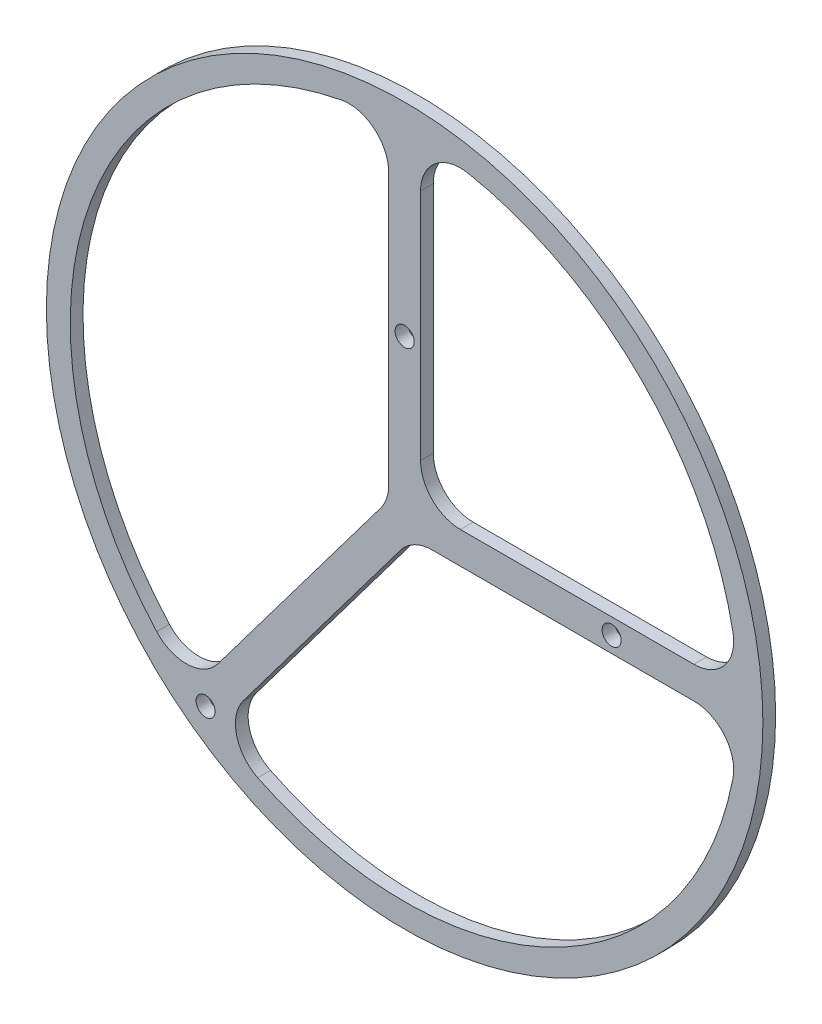
SolidWorks part; units mm, degrees
ref_plane "Front Plane" through (0, 0, 0) normal (1, 0, 0) x (0, 1, 0)
ref_plane "Top Plane" through (0, 0, 0) normal (0, 0, 1) x (0, 1, 0)
ref_plane "Right Plane" through (0, 0, 0) normal (0, 1, 0) x (-1, 0, 0)
sketch "Sketch5" plane through (0, 0, 0) normal (0, 0, 1) x (0, 1, 0)
  circle A0 centre (0, 0) radius 45
  dimension "D1" = 90
extrude "Boss-Extrude2" add sketch "Sketch5" along normal blind 1.6
sketch "Sketch2" plane through (0, 0, 0) normal (0, 0, 1) x (0, 1, 0)
  line L0 (19.5, 0) -> (0, 0) construction
  line L1 (0, 0) -> (0, -26) construction
  circle A0 centre (0, 0) radius 45
  point P0 (-42, -26)
  point P1 (0, -26)
  point P2 (19.5, 0)
  point P3 (-33.2215, 25)
  dimension "D6" = 90
  dimension "D1" = 42
  dimension "D2" = 61.5
  dimension "D3" = 26
  dimension "D4" = 51
  dimension "D5" = 51.75
hole_wizard "M2 Clearance Hole2" positions "Sketch2" profile "Sketch7" hole size "M2" standard "ANSI Metric"
sketch "Sketch7" plane through (-25, -33.2215, 0) normal (1, 0, 0) x (0, 1, 0)
  line L0 (0, 0) -> (0, 2.321)
  line L1 (0, 2.321) -> (1.2, 1.6)
  line L2 (1.2, 1.6) -> (1.2, 0)
  line L5 (1.2, 0) -> (0, 0)
  line L10 (0, 2.321) -> (-1.2, 1.6) construction
  line L11 (0, -6.35) -> (0, 107.95) construction
  dimension "Hole Dia." = 2.4
  dimension "Hole Depth" = 1.6
  dimension "Drill Angle" = 118
sketch "Sketch8" plane through (0, 0, 1.6) normal (0, 0, 1) x (1, 0, 0)
  line L0 (-25, -33.2215) -> (0, 0) construction
  line L1 (0, 0) -> (26, 0) construction
  line L2 (0, 0) -> (0, 19.5) construction
  line L3 (-25, -33.2215) -> (-25.2542, -33.5593) construction
  line L4 (26, 0) -> (42, 0) construction
  line L5 (0, 19.5) -> (0, 42) construction
  line L6 (-26.5981, -32.0189) -> (-26.8236, -32.3186)
  line L7 (-26.5981, -32.0189) -> (-2, 0.6685)
  line L8 (2, 2) -> (26, 2)
  line L9 (26, 2) -> (41.9524, 2)
  line L10 (-2, 0.6685) -> (-2, 19.5)
  line L11 (-2, 19.5) -> (-2, 41.9524)
  line L12 (-23.4019, -34.4241) -> (-23.6275, -34.7238)
  line L13 (-23.4019, -34.4241) -> (0.998, -2)
  line L14 (0.998, -2) -> (26, -2)
  line L15 (26, -2) -> (41.9524, -2)
  line L16 (2, 2) -> (2, 19.5)
  line L17 (2, 19.5) -> (2, 41.9524)
  line L19 (-26.5981, -32.0189) -> (-1.5981, 1.2026) construction
  line L20 (-2, 0) -> (-2, 19.5) construction
  line L21 (-23.4019, -34.4241) -> (1.5981, -1.2026) construction
  line L22 (0, -2) -> (26, -2) construction
  line L23 (2, 0) -> (2, 19.5) construction
  line L24 (0, 2) -> (26, 2) construction
  line L25 (-23.4019, -34.4241) -> (-23.6561, -34.7619) construction
  line L26 (-26.5981, -32.0189) -> (-26.8523, -32.3567) construction
  line L27 (26, -2) -> (42, -2) construction
  line L28 (26, 2) -> (42, 2) construction
  line L29 (-2, 19.5) -> (-2, 42) construction
  line L30 (2, 19.5) -> (2, 42) construction
  circle A2 centre (0, 0) radius 42
  circle A3 centre (0, 0) radius 42
  circle A14 centre (-25, -33.2215) radius 1.2 construction
  circle A17 centre (26, 0) radius 1.2 construction
  circle A19 centre (0, 19.5) radius 1.2 construction
  circle A20 centre (-25, -33.2215) radius 1.2
  circle A22 centre (26, 0) radius 1.2
  circle A23 centre (0, 19.5) radius 1.2
  dimension "D1" = 3
  dimension "D5" = 2
  dimension "D6" = 2
extrude "Cut-Extrude1" cut sketch "Sketch8" against normal through all contours L12 A3 L15 L14 L13 | L11 A3 L6 L7 L10 | L9 A3 L17 L16 L8
fillet "Fillet1" radius 5 9 edges at (-23.6275, -34.7238, 0.8) (-26.8236, -32.3186, 0.8) (-2, 0.6685, 0.8) (2, 2, 0.8) (0.998, -2, 0.8) (41.9524, -2, 0.8) (41.9524, 2, 0.8) (-2, 41.9524, 0.8) (2, 41.9524, 0.8)
